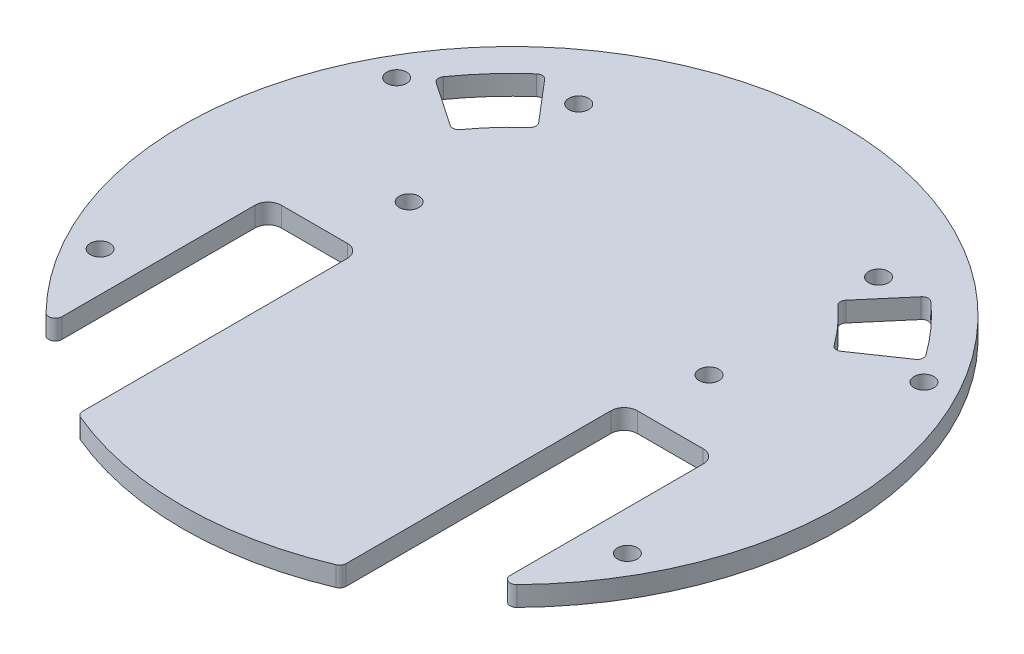
SolidWorks part; units mm, degrees
material "Cast Alloy Steel"
ref_plane "Front Plane" through (0, 0, 0) normal (0, 0, 1) x (1, 0, 0)
ref_plane "Top Plane" through (0, 0, 0) normal (0, 1, 0) x (1, 0, 0)
ref_plane "Right Plane" through (0, 0, 0) normal (1, 0, 0) x (0, 0, -1)
sketch "Sketch1" plane through (0, 0, 0) normal (0, 1, 0) x (1, 0, 0)
  circle A0 centre (0, 0) radius 50
  dimension "D1" = 100
extrude "Boss-Extrude1" add sketch "Sketch1" along normal blind 3
sketch "Sketch2" plane through (0, 3, 0) normal (0, 1, 0) x (1, 0, 0)
  line L0 (0, 50) -> (0, 20) construction
  line L2 (22.75, 7.14) -> (-22.75, 7.14) construction
  line L3 (22.75, 7.14) -> (22.75, 32.86) construction
  line L4 (22.75, 32.86) -> (-22.75, 32.86) construction
  line L5 (-22.75, 7.14) -> (-22.75, 32.86) construction
  line L6 (22.75, 7.14) -> (-22.75, 32.86) construction
  line L7 (22.75, 32.86) -> (-22.75, 7.14) construction
  circle A0 centre (0, 0) radius 50 construction
  circle A1 centre (-22.75, 32.86) radius 1.5
  circle A2 centre (22.75, 32.86) radius 1.5
  circle A3 centre (22.75, 7.14) radius 1.5
  circle A4 centre (-22.75, 7.14) radius 1.5
  dimension "D3" = 3
  dimension "D1" = 45.5
  dimension "D2" = 25.72
  dimension "D4" = 30
extrude "Cut-Extrude1" cut sketch "Sketch2" against normal blind 10
sketch "Sketch3" plane through (0, 0, 0) normal (0, -1, 0) x (1, 0, 0)
  line L0 (0, 0) -> (0, 50) construction
  line L1 (-34, 48) -> (-20, 48)
  line L2 (-34, 48) -> (-34, 3)
  line L3 (-34, 3) -> (-20, 3)
  line L4 (-20, 48) -> (-20, 3)
  line L5 (34, 3) -> (20, 3)
  line L6 (20, 48) -> (20, 3)
  line L7 (34, 48) -> (20, 48)
  line L8 (34, 48) -> (34, 3)
  circle A0 centre (0, 0) radius 50 construction
  dimension "D1" = 14
  dimension "D2" = 45
  dimension "D3" = 20
  dimension "D4" = 3
extrude "Cut-Extrude2" cut sketch "Sketch3" against normal blind 10
fillet "Fillet1" radius 1 4 edges at (20, 1.5, 45.8258) (34, 1.5, 36.6606) (-20, 1.5, 45.8258) (-34, 1.5, 36.6606)
sketch "Sketch4" plane through (0, 0, 0) normal (0, -1, 0) x (1, 0, 0)
  line L1 (40, -22.5) -> (-40, -22.5) construction
  line L2 (40, -22.5) -> (40, 22.5) construction
  line L3 (40, 22.5) -> (-40, 22.5) construction
  line L4 (-40, -22.5) -> (-40, 22.5) construction
  line L5 (40, -22.5) -> (-40, 22.5) construction
  line L6 (40, 22.5) -> (-40, -22.5) construction
  circle A0 centre (-40, 22.5) radius 1.5
  circle A1 centre (-40, -22.5) radius 1.5
  circle A2 centre (40, -22.5) radius 1.5
  circle A3 centre (40, 22.5) radius 1.5
  point P0 (0, 0)
  dimension "D3" = 3
  dimension "D1" = 80
  dimension "D2" = 45
extrude "Cut-Extrude3" cut sketch "Sketch4" against normal blind 10
sketch "Sketch5" plane through (0, 0, 0) normal (0, -1, 0) x (1, 0, 0)
  line L4 (0, 50) -> (0, -50) construction
  arc A2 (19.3878, 46.0881) -> (-19.3878, 46.0881) centre (0, 0) ccw construction
  arc A3 (-35.7143, 34.9927) -> (35.7143, 34.9927) centre (0, 0) ccw construction
fillet "Fillet2" radius 2 4 edges at (20, 1.5, 3) (-34, 1.5, 3) (34, 1.5, 3) (-20, 1.5, 3)
sketch "Sketch6" plane through (0, 3, 0) normal (0, 1, 0) x (1, 0, 0)
  line L0 (0, 0) -> (32.4326, 38.0543) construction
  line L1 (0, -50) -> (0, 50) construction
  line L2 (0, 0) -> (0, 50) construction
  line L3 (23.31, 27.3504) -> (28.5674, 33.5191)
  line L4 (0, 0) -> (41.2764, 28.218) construction
  line L5 (29.6663, 20.2809) -> (36.3573, 24.8551)
  line L6 (-23.31, 27.3504) -> (-28.5674, 33.5191)
  line L7 (-29.6663, 20.2809) -> (-36.3573, 24.8551)
  arc A0 (35.7143, -34.9927) -> (-35.7143, -34.9927) centre (0, 0) ccw construction
  circle A1 centre (22.75, 32.86) radius 1.5 construction
  circle A2 centre (40, 22.5) radius 1.5 construction
  arc A3 (29.9201, 33.6123) -> (36.5933, 26.1903) centre (0, 0) cw
  arc A4 (23.3978, 26.0296) -> (28.3622, 20.5081) centre (0, 0) cw
  arc A5 (-23.3978, 26.0296) -> (-28.3622, 20.5081) centre (0, 0) ccw
  arc A6 (-29.9201, 33.6123) -> (-36.5933, 26.1903) centre (0, 0) ccw
  arc A7 (28.3622, 20.5081) -> (29.6663, 20.2809) centre (29.1309, 21.064) ccw
  arc A8 (36.5933, 26.1903) -> (36.3573, 24.8551) centre (35.8219, 25.6382) cw
  arc A9 (29.9201, 33.6123) -> (28.5674, 33.5191) centre (29.2894, 32.9038) ccw
  arc A10 (23.3978, 26.0296) -> (23.31, 27.3504) centre (24.032, 26.7351) cw
  arc A11 (-28.3622, 20.5081) -> (-29.6663, 20.2809) centre (-29.1309, 21.064) cw
  arc A12 (-23.3978, 26.0296) -> (-23.31, 27.3504) centre (-24.032, 26.7351) ccw
  arc A13 (-28.5674, 33.5191) -> (-29.9201, 33.6123) centre (-29.2894, 32.9038) ccw
  arc A14 (-36.5933, 26.1903) -> (-36.3573, 24.8551) centre (-35.8219, 25.6382) ccw
  point P24 (28.8935, 19.7526)
  point P27 (37.1488, 25.3962)
  point P30 (29.1893, 34.2488)
  point P33 (22.7028, 26.638)
  point P36 (-28.8935, 19.7526)
  point P39 (-22.7028, 26.638)
  point P42 (-29.1893, 34.2488)
  point P45 (-37.1488, 25.3962)
  dimension "D4" = 5
  dimension "D5" = 0.9486
  dimension "D1" = 4
  dimension "D2" = 4
  dimension "D3" = 10
extrude "Cut-Extrude5" cut sketch "Sketch6" against normal blind 3
